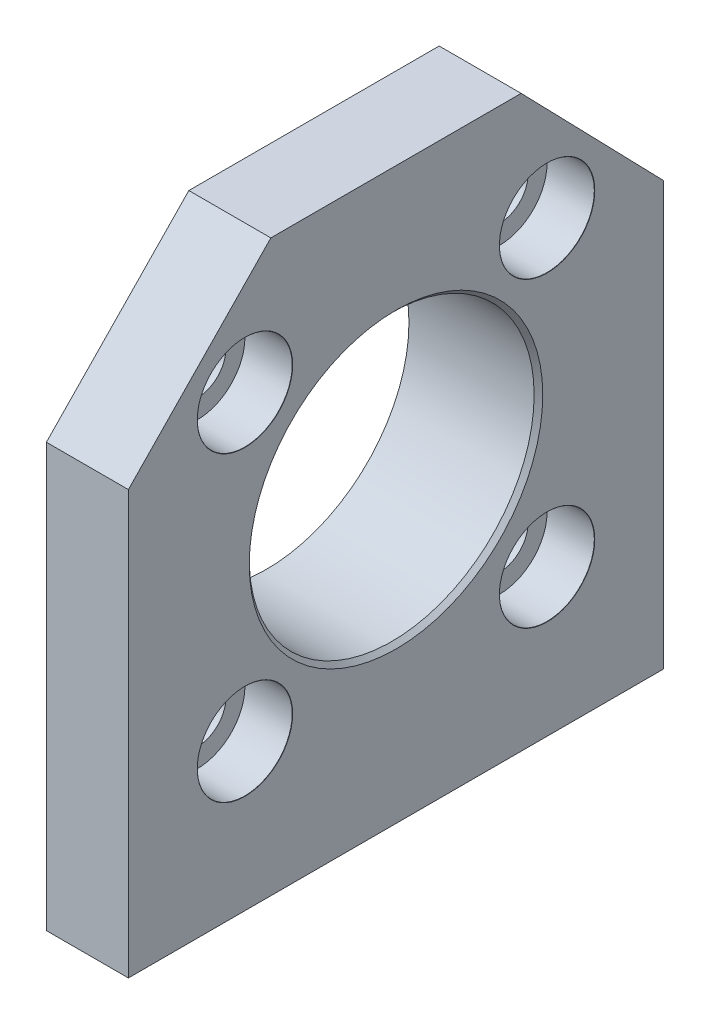
SolidWorks part; units mm, degrees
ref_plane "Plano frontal" through (0, 0, 0) normal (0, 0, 1) x (1, 0, 0)
ref_plane "Plano superior" through (0, 0, 0) normal (0, 1, 0) x (1, 0, 0)
ref_plane "Plano direito" through (0, 0, 0) normal (1, 0, 0) x (0, 0, -1)
sketch "Esboço1" plane through (0, 0, 0) normal (1, 0, 0) x (0, 0, -1)
  line L0 (0, 49) -> (16.5, 66)
  line L1 (0, 0) -> (62, 0)
  line L2 (0, 0) -> (0, 49)
  line L3 (0, 49) -> (62, 49)
  line L4 (62, 0) -> (62, 49)
  line L5 (16.5, 66) -> (45.5, 66)
  line L6 (45.5, 66) -> (62, 49)
  line L7 (31, 0) -> (31, 66) construction
  point P5 (31, 66)
  dimension "D1" = 66
  dimension "D2" = 49
  dimension "D3" = 62
  dimension "D4" = 29
extrude "Ressalto-extrusão1" add sketch "Esboço1" against normal blind 9.5 contours L3 L7 L5 L0 | L7 L3 L6 L5 | L1 L7 L3 L2 | L7 L1 L4 L3
hole_wizard "Rebaixo para parafuso com cabeça redonda de M61" positions "Esboço3" profile "Esboço4" counterbore size "M6" standard "ISO" end condition through all
sketch "Esboço3" plane through (0, 0, 0) normal (1, 0, 0) x (0, 0, -1)
  line L0 (0, 0) -> (62, 0) construction
  line L1 (16.5, 66) -> (45.5, 66) construction
  point P0 (13.5, 52)
  point P2 (48.5, 52)
  point P4 (48.5, 17)
  point P6 (13.5, 17)
  point P17 (31, 66)
  dimension "D1" = 35
  dimension "D2" = 35
  dimension "D3" = 17
  dimension "D4" = 17.5
sketch "Esboço4" plane through (0, 52, -13.5) normal (0, 1, 0) x (0, 0, -1)
  line L0 (0, 0) -> (0, 9.5)
  line L1 (0, 9.5) -> (3.3, 9.5)
  line L3 (3.3, 9.5) -> (3.3, 5.5)
  line L4 (5.5, 5.5) -> (3.3, 5.5)
  line L5 (5.5, 5.5) -> (5.5, 0.025)
  line L6 (5.5, 0.025) -> (5.525, 0)
  line L7 (5.525, 0) -> (0, 0)
  line L8 (-5.5, 0.025) -> (-5.525, 0) construction
  line L11 (0, -6.35) -> (0, 107.95) construction
  dimension "Thru Hole Dia." = 6.6
  dimension "Thru Hole Depth" = 9.5
  dimension "C'Bore Dia." = 11
  dimension "C'Bore Depth" = 5.5
  dimension "Near C'Sink Dia." = 11.05
  dimension "Near C'Sink Angle" = 90
sketch "Esboço8" plane through (-9.5, 0, 0) normal (-1, 0, 0) x (0, 0, 1)
  circle A0 centre (-31, 34.5) radius 19.9
  circle A1 centre (-13.5, 52) radius 3.3 construction
  circle A2 centre (-48.5, 17) radius 3.3 construction
  dimension "D1" = 39.8
  dimension "D3" = 17.5
  dimension "D2" = 17.5
extrude "Ressalto-extrusão2" add sketch "Esboço8" along normal blind 5.5
sketch "Esboço5" plane through (0, 0, 0) normal (1, 0, 0) x (0, 0, -1)
  circle A0 centre (31, 34.5) radius 16.5
  circle A1 centre (13.5, 52) radius 3.3 construction
  circle A2 centre (13.5, 17) radius 5.5 construction
  dimension "D1" = 33
  dimension "D2" = 17.5
  dimension "D3" = 17.5
extrude "Corte-extrusão1" cut sketch "Esboço5" against normal through all
chamfer "Chanfro1" distance 0.5 angle 45 1 edges at (0, 34.5, -47.5)
